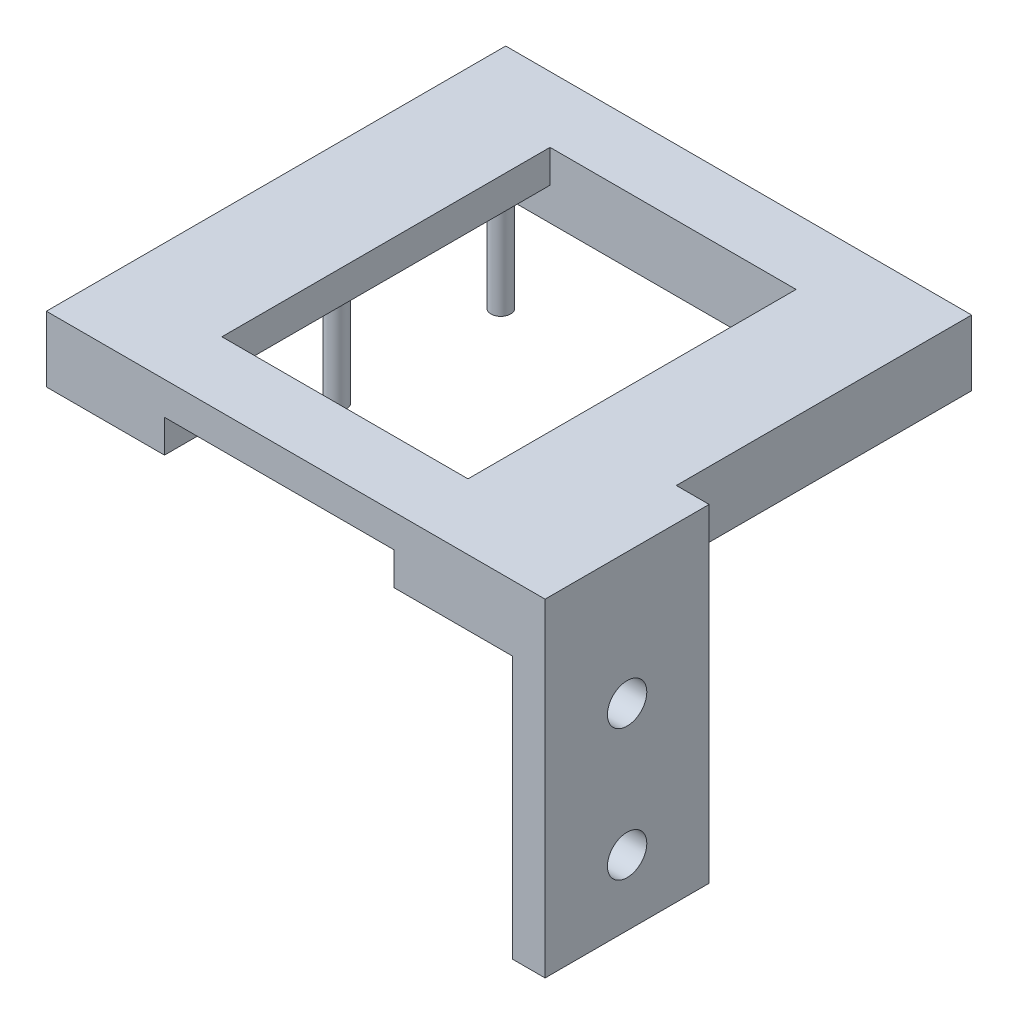
SolidWorks part; units mm, degrees
ref_plane "Front Plane" through (0, 0, 0) normal (0, 0, 1) x (1, 0, 0)
ref_plane "Top Plane" through (0, 0, 0) normal (0, 1, 0) x (1, 0, 0)
ref_plane "Right Plane" through (0, 0, 0) normal (1, 0, 0) x (0, 0, -1)
sketch "Sketch1" plane through (0, 0, 0) normal (0, 1, 0) x (1, 0, 0)
  line L0 (-5.08, 30.48) -> (30.988, 30.48)
  line L1 (0, 0) -> (4.064, 0)
  line L2 (0, 0) -> (0, 25.4)
  line L3 (0, 25.4) -> (25.908, 25.4)
  line L4 (25.908, 0) -> (25.908, 25.4)
  line L5 (30.988, -5.08) -> (30.988, 30.48)
  line L6 (-5.08, -5.08) -> (4.064, -5.08)
  line L7 (-5.08, -5.08) -> (-5.08, 30.48)
  line L8 (4.064, -5.08) -> (4.064, 0)
  line L9 (21.844, -5.08) -> (21.844, 0)
  line L10 (21.844, 0) -> (25.908, 0)
  line L11 (0, 0) -> (25.908, 0) construction
  line L12 (21.844, -5.08) -> (30.988, -5.08)
  line L13 (-5.08, -5.08) -> (30.988, -5.08) construction
  dimension "D1" = 25.908
  dimension "D2" = 25.4
  dimension "D3" = 5.08
  dimension "D4" = 4.064
  dimension "D5" = 17.78
extrude "Boss-Extrude1" add sketch "Sketch1" along normal blind 2.54
sketch "Sketch4" plane through (0, 2.54, 0) normal (0, 1, 0) x (1, 0, 0)
  line L0 (30.988, 30.48) -> (-5.08, 30.48) construction
  line L1 (-5.08, 30.48) -> (30.988, 30.48)
  line L2 (-5.08, 30.48) -> (-5.08, -5.08)
  line L3 (-5.08, -5.08) -> (30.988, -5.08)
  line L4 (30.988, 30.48) -> (30.988, -5.08)
extrude "Boss-Extrude2" add sketch "Sketch4" along normal blind 2.54
sketch "Sketch5" plane through (0, 2.54, 0) normal (0, -1, 0) x (1, 0, 0)
  line L0 (0, -25.4) -> (25.908, -25.4) construction
  line L1 (3.429, -25.4) -> (22.479, -25.4)
  line L2 (3.429, -25.4) -> (3.429, 0)
  line L3 (3.429, 0) -> (22.479, 0)
  line L4 (22.479, -25.4) -> (22.479, 0)
  line L5 (25.908, -25.4) -> (25.908, 0) construction
  line L6 (4.064, 0) -> (0, 0) construction
  dimension "D1" = 19.05
  dimension "D2" = 3.429
extrude "Cut-Extrude1" cut sketch "Sketch5" against normal through all
sketch "Sketch6" plane through (30.988, 0, 0) normal (1, 0, 0) x (0, 0, -1)
  line L1 (-5.08, 5.08) -> (30.48, 5.08)
  line L2 (-5.08, 5.08) -> (-5.08, 0)
  line L3 (-5.08, 0) -> (30.48, 0)
  line L4 (30.48, 5.08) -> (30.48, 0)
sketch "Sketch7" plane through (0, 2.54, 0) normal (0, -1, 0) x (1, 0, 0)
  line L0 (0, -25.4) -> (3.429, -25.4) construction
  line L1 (0, 0) -> (0, -25.4) construction
  line L2 (25.908, -25.4) -> (25.908, 0) construction
  line L3 (22.479, -25.4) -> (25.908, -25.4) construction
  circle A0 centre (2.159, -10.16) radius 0.762
  circle A1 centre (2.159, -22.86) radius 0.762
  circle A2 centre (23.749, -10.16) radius 0.762
  circle A3 centre (23.749, -22.86) radius 0.762
  dimension "D1" = 1.524
  dimension "D2" = 1.524
  dimension "D7" = 1.524
  dimension "D8" = 1.524
  dimension "D3" = 12.7
  dimension "D4" = 2.54
  dimension "D5" = 2.159
  dimension "D6" = 2.159
  dimension "D9" = 12.7
  dimension "D10" = 2.159
  dimension "D11" = 2.159
  dimension "D12" = 2.54
extrude "Boss-Extrude3" add sketch "Sketch7" along normal blind 7.62
sketch "Sketch9" plane through (30.988, 0, 0) normal (1, 0, 0) x (0, 0, -1)
  line L0 (-5.08, 5.08) -> (30.48, 5.08) construction
  line L1 (-5.08, -20.32) -> (7.62, -20.32)
  line L2 (-5.08, -20.32) -> (-5.08, 5.08)
  line L3 (-5.08, 5.08) -> (7.62, 5.08)
  line L4 (7.62, -20.32) -> (7.62, 5.08)
  line L6 (-5.08, 5.08) -> (-5.08, 0) construction
  circle A0 centre (1.27, -5.08) radius 1.524
  circle A1 centre (1.27, -15.24) radius 1.524
  dimension "D3" = 3.048
  dimension "D4" = 3.048
  dimension "D1" = 25.4
  dimension "D2" = 12.7
  dimension "D5" = 10.16
  dimension "D6" = 10.16
  dimension "D7" = 6.35
  dimension "D8" = 6.35
extrude "Boss-Extrude4" add sketch "Sketch9" along normal blind 2.54
